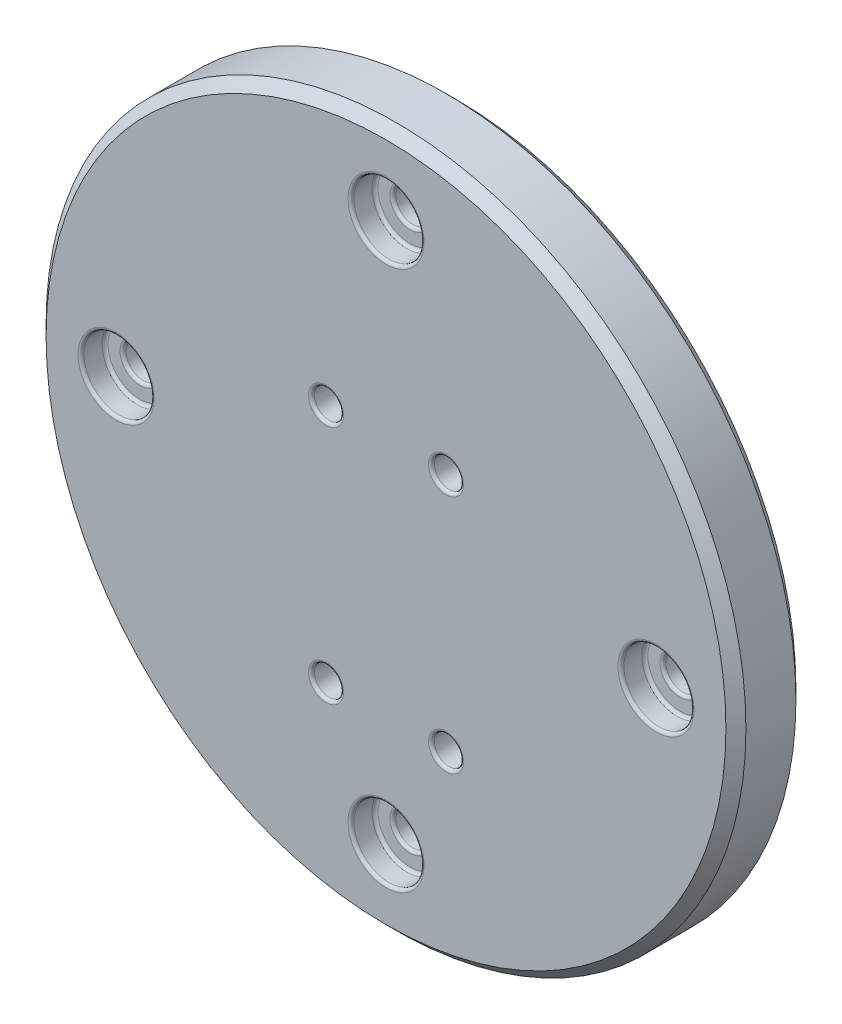
SolidWorks part; units mm, degrees
ref_plane "정면" through (0, 0, 0) normal (0, 0, 1) x (1, 0, 0)
ref_plane "윗면" through (0, 0, 0) normal (0, 1, 0) x (1, 0, 0)
ref_plane "우측면" through (0, 0, 0) normal (1, 0, 0) x (0, 0, -1)
sketch "스케치1" plane through (0, 0, 0) normal (0, 0, 1) x (1, 0, 0)
  circle A0 centre (0, 0) radius 35
  dimension "D1" = 70
extrude "보스-돌출1" add sketch "스케치1" along normal mid plane 7
hole_wizard "M2.5 남비 머리 나사용 카운터보어1" positions "스케치3" profile "스케치4" counterbore size "M2.5" standard "ISO" end condition through all
sketch "스케치3" plane through (0, 0, -3.5) normal (0, 0, -1) x (-1, 0, 0)
  point P0 (-6, 8)
  point P3 (6, 8)
  point P6 (-6, -16)
  point P9 (6, -16)
sketch "스케치4" plane through (6, 8, -3.5) normal (1, 0, 0) x (0, 1, 0)
  line L0 (0, 0) -> (0, 7)
  line L1 (0, 7) -> (1.45, 7)
  line L3 (1.45, 7) -> (1.45, 3)
  line L4 (1.45, 3) -> (3, 3)
  line L5 (3, 3) -> (3, 0)
  line L7 (3, 0) -> (0, 0)
  line L11 (0, -6.35) -> (0, 107.95) construction
  dimension "관통 구멍 지름" = 2.9
  dimension "관통 구멍 깊이" = 7
  dimension "카운터보어 지름" = 6
  dimension "카운터보어 깊이" = 3
fillet "필렛1" radius 0.3 16 edges at (4.55, 8, -0.5) (4.55, 8, 3.5) (-9, 8, -3.5) (-9, 8, -0.5) (-7.45, 8, -0.5) (-7.45, 8, 3.5) (3, -16, -3.5) (3, -16, -0.5) (4.55, -16, -0.5) (4.55, -16, 3.5) (-9, -16, -3.5) (-9, -16, -0.5) (-7.45, -16, -0.5) (-7.45, -16, 3.5) (3, 8, -0.5) (3, 8, -3.5)
sketch "스케치9" plane through (0, 0, 3.5) normal (0, 0, 1) x (1, 0, 0)
  line L8 (0, -27) -> (27, 0)
  line L9 (0, -27) -> (-27, 0)
  line L10 (27, 0) -> (0, 27)
  line L11 (-27, 0) -> (0, 27)
  line L12 (-27, 0) -> (27, 0) construction
  line L13 (0, 27) -> (0, -27) construction
  point P0 (26.8607, 0)
  point P3 (0, 0)
  dimension "D1" = 54
hole_wizard "M3 남비 머리 나사용 카운터보어2" positions "스케치10" profile "스케치11" counterbore size "M3" standard "ISO" end condition through all
sketch "스케치10" plane through (0, 0, 3.5) normal (0, 0, 1) x (1, 0, 0)
  point P0 (0, 27)
  point P3 (27, 0)
  point P6 (0, -27)
  point P9 (-27, 0)
sketch "스케치11" plane through (0, 27, 3.5) normal (1, 0, 0) x (0, -1, 0)
  line L0 (0, 0) -> (0, 7)
  line L1 (0, 7) -> (1.7, 7)
  line L3 (1.7, 7) -> (1.7, 2.4)
  line L4 (1.7, 2.4) -> (3.5, 2.4)
  line L5 (3.5, 2.4) -> (3.5, 0)
  line L7 (3.5, 0) -> (0, 0)
  line L11 (0, -6.35) -> (0, 107.95) construction
  dimension "관통 구멍 지름" = 3.4
  dimension "관통 구멍 깊이" = 7
  dimension "카운터보어 지름" = 7
  dimension "카운터보어 깊이" = 2.4
fillet "필렛2" radius 0.3 16 edges at (1.7, -27, -3.5) (28.7, 0, -3.5) (1.7, 27, -3.5) (-25.3, 0, -3.5) (3.5, 27, 1.1) (1.7, 27, 1.1) (30.5, 0, 1.1) (28.7, 0, 1.1) (-23.5, 0, 1.1) (-25.3, 0, 1.1) (1.7, -27, 1.1) (3.5, -27, 3.5) (3.5, -27, 1.1) (30.5, 0, 3.5) (3.5, 27, 3.5) (-23.5, 0, 3.5)
chamfer "모따기1" distance 1 angle 45 2 edges at (35, 0, -3.5) (35, 0, 3.5)
